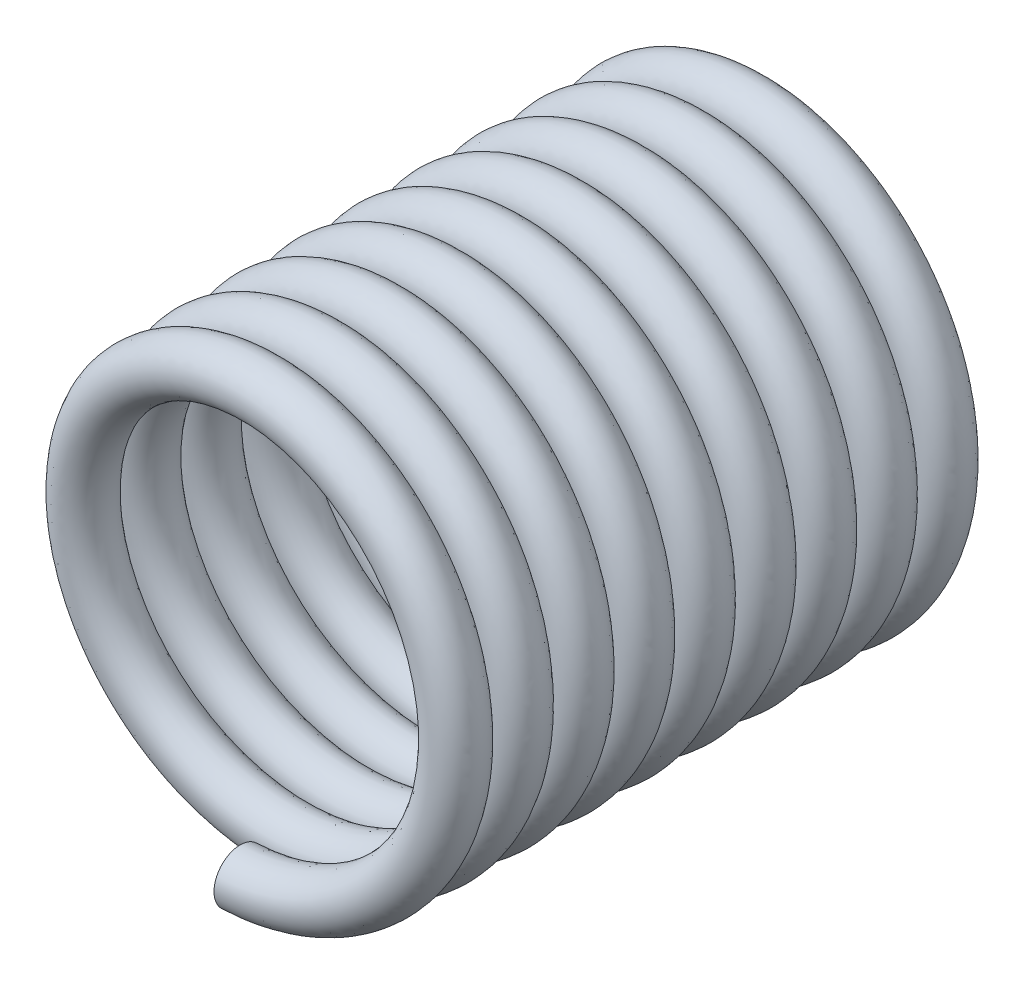
SolidWorks part; units mm, degrees
material "ASTM A36 Steel"
ref_plane "Front Plane" through (0, 0, 0) normal (0, 0, 1) x (1, 0, 0)
ref_plane "Top Plane" through (0, 0, 0) normal (0, 1, 0) x (1, 0, 0)
ref_plane "Right Plane" through (0, 0, 0) normal (1, 0, 0) x (0, 0, -1)
sketch "Sketch1" plane through (0, 0, 0) normal (0, 0, 1) x (1, 0, 0)
  circle A0 centre (0, 0) radius 4.0005
  dimension "D1" = 8.001
curve "Helix/Spiral1" pitch 1.1437 height 10.0076 turns 8.75
ref_plane "Plane1" through (0, -4.0005, 10.0076) normal (-0.999, 0, 0.0455) x (0.0454, -0.015, 0.9989)
sketch "Sketch2" plane through (0, -4.0005, 10.0076) normal (-0.999, 0, 0.0455) x (0.0454, -0.015, 0.9989)
  circle A0 centre (0.0016, 0.2066) radius 0.4953
  dimension "D1" = 0.9906
sweep "Sweep1" add profiles "Sketch2" path "Helix/Spiral1"
sketch "Sketch3" plane through (0, -4.0005, 10.0076) normal (-0.999, 0, 0.0455) x (0.0454, -0.015, 0.9989)
  circle A1 centre (0.0016, 0.2066) radius 0.4826
extrude "Boss-Extrude1" [suppressed] add sketch "Sketch3" along normal blind 34.925
sketch "Sketch4" plane through (0, 0, 0) normal (0, -0.999, -0.0455) x (1, 0, 0)
  circle A0 centre (-3.7939, 0.0047) radius 0.4953
  circle A1 centre (-3.7939, 0.0047) radius 0.4953 construction
extrude "Boss-Extrude2" [suppressed] add sketch "Sketch4" along normal blind 34.925
